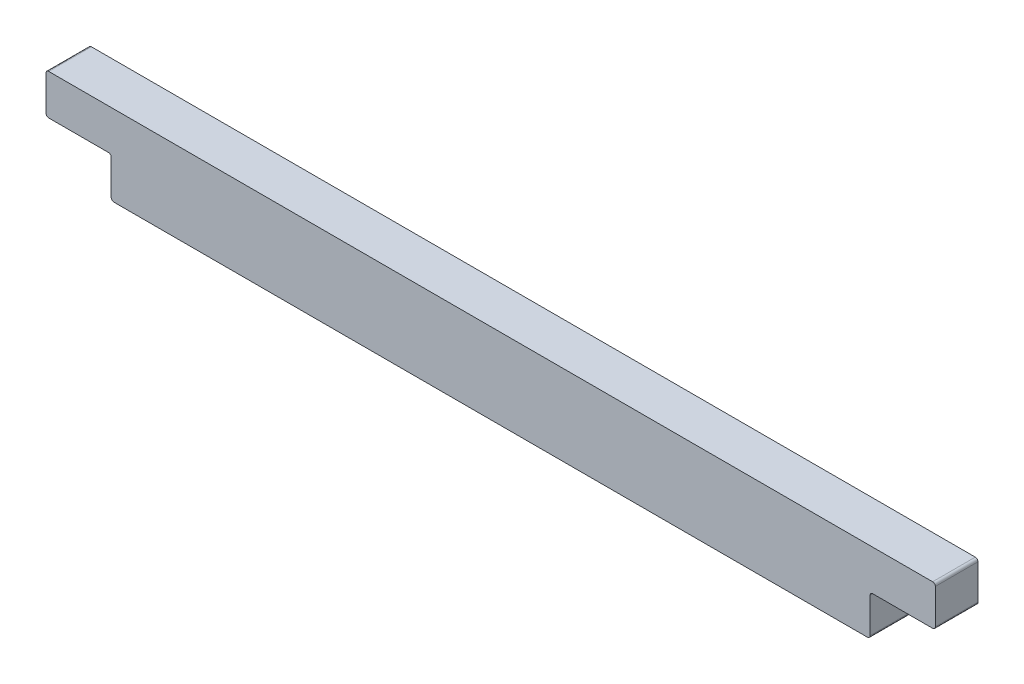
SolidWorks part; units mm, degrees
ref_plane "Front Plane" through (0, 0, 0) normal (0, 0, 1) x (1, 0, 0)
ref_plane "Top Plane" through (0, 0, 0) normal (0, 1, 0) x (1, 0, 0)
ref_plane "Right Plane" through (0, 0, 0) normal (1, 0, 0) x (0, 0, -1)
sketch "Sketch1" plane through (0, 0, 0) normal (0, 0, 1) x (1, 0, 0)
  line L1 (-33.08, -3) -> (33.08, -3)
  line L2 (-33.08, -3) -> (-33.08, 3)
  line L3 (-33.08, 3) -> (33.08, 3)
  line L4 (33.08, -3) -> (33.08, 3)
  line L5 (-33.08, -3) -> (33.08, 3) construction
  line L6 (-33.08, 3) -> (33.08, -3) construction
  point P0 (0, 0)
  dimension "D1" = 66.16
  dimension "D2" = 6
extrude "Boss-Extrude1" add sketch "Sketch1" along normal blind 3.175
sketch "Sketch2" plane through (0, 0, 3.175) normal (0, 0, 1) x (1, 0, 0)
  line L1 (-33.08, -3) -> (-28.23, -3)
  line L2 (-33.08, -3) -> (-33.08, 0)
  line L3 (-33.08, 0) -> (-28.23, 0)
  line L4 (-28.23, -3) -> (-28.23, 0)
  line L5 (33.08, -3) -> (28.23, -3)
  line L6 (33.08, -3) -> (33.08, 0)
  line L7 (33.08, 0) -> (28.23, 0)
  line L8 (28.23, -3) -> (28.23, 0)
  point P10 (-30.655, 0)
  dimension "D1" = 3
  dimension "D2" = 4.85
extrude "Cut-Extrude1" cut sketch "Sketch2" against normal through all
fillet "Fillet1" radius 0.2 8 edges at (-28.23, 0, 1.5875) (-28.23, -3, 1.5875) (28.23, 0, 1.5875) (33.08, 0, 1.5875) (33.08, 3, 1.5875) (-33.08, 3, 1.5875) (-33.08, 0, 1.5875) (28.23, -3, 1.5875)
